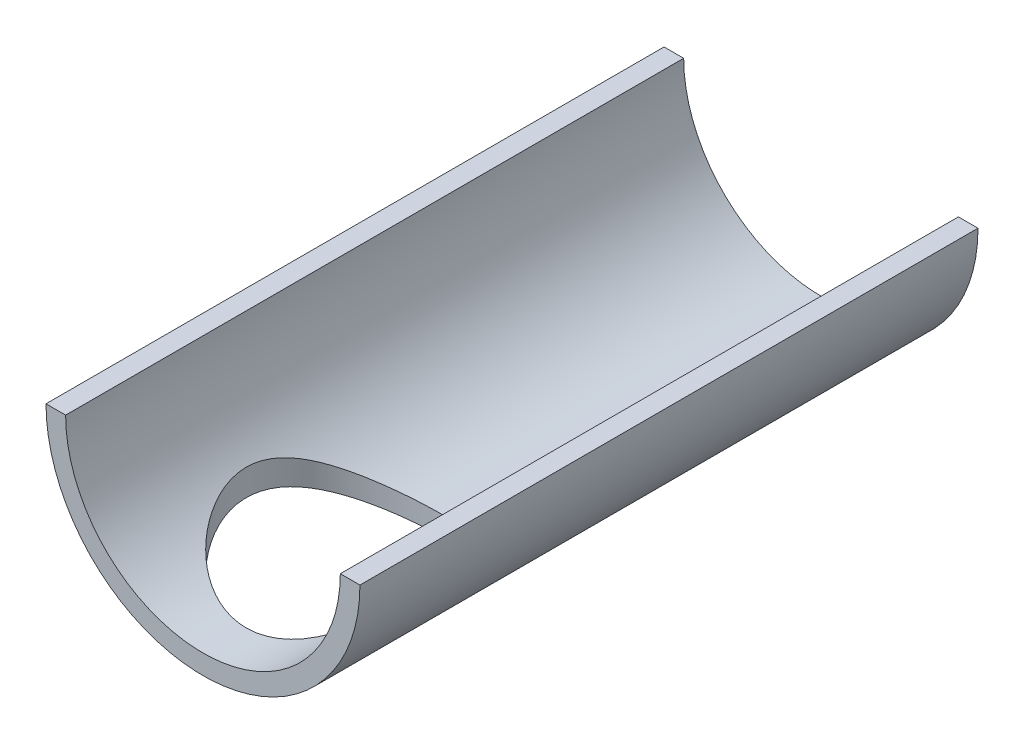
SolidWorks part; units mm, degrees
material "Acrylic (Medium-high impact)"
ref_plane "Front Plane" through (0, 0, 0) normal (0, 0, 1) x (1, 0, 0)
ref_plane "Top Plane" through (0, 0, 0) normal (0, 1, 0) x (1, 0, 0)
ref_plane "Right Plane" through (0, 0, 0) normal (1, 0, 0) x (0, 0, -1)
sketch "Sketch1" plane through (0, 0, 0) normal (0, 0, 1) x (1, 0, 0)
  circle A0 centre (0, 0) radius 25.4
  circle A1 centre (0, 0) radius 22.225
  dimension "D1" = 50.8
  dimension "D2" = 44.45
extrude "Boss-Extrude1" add sketch "Sketch1" along normal blind 914.4
sketch "Sketch2" plane through (0, 0, 0) normal (0, 0, -1) x (-1, 0, 0)
  circle A0 centre (0, 0) radius 25.4 construction
  circle A1 centre (0, 0) radius 25.4
extrude "Cut-Extrude1" cut sketch "Sketch2" against normal through all from offset 100.0125 offset against normal yes
sketch "Sketch4" plane through (0, 0, 0) normal (0, 0, 1) x (1, 0, 0)
  line L0 (-25.4, 0) -> (25.4, 0)
  circle A0 centre (0, 0) radius 25.4 construction
  arc A1 (25.4, 0) -> (-25.4, 0) centre (0, 0) ccw
extrude "Cut-Extrude3" cut sketch "Sketch4" along normal through all
ref_plane "Plane1" through (0, -25.4, 0) normal (0, -1, 0) x (-1, 0, 0)
ref_plane "Plane3" through (0, -22.225, 0) normal (0, 1, 0) x (1, 0, 0)
ref_plane "Plane2" through (0, 0, 15.875) normal (0, 0, -1) x (-1, 0, 0)
sketch "Sketch6" plane through (0, 0, 0) normal (0, 1, 0) x (1, 0, 0)
  line L0 (-25.4, -77.1218) -> (25.4, -77.1218) construction
  line L1 (-25.4, -100.0125) -> (-25.4, 0) construction
  line L2 (25.4, -100.0125) -> (25.4, 0) construction
  line L3 (-18.1607, -76.1596) -> (-54.2354, -161.1882) construction
  line L4 (-20.1702, -168.4306) -> (12.0683, -92.4439) construction
  line L5 (-18.1607, -76.1596) -> (-54.2354, -161.1882) construction
  line L6 (-20.1702, -168.4306) -> (12.0683, -92.4439) construction
  line L7 (12.0683, -92.4439) -> (25.4, -61.0208) construction
  line L8 (-18.1607, -76.1596) -> (25.4, 26.5135) construction
  line L9 (-15.7363, -70.4454) -> (15.7363, -83.7982) construction
  circle A0 centre (0, -77.1218) radius 15.875
  point P21 (0, -77.1218)
  dimension "D1" = 31.75
extrude "Cut-Extrude5" cut sketch "Sketch6" against normal through all
